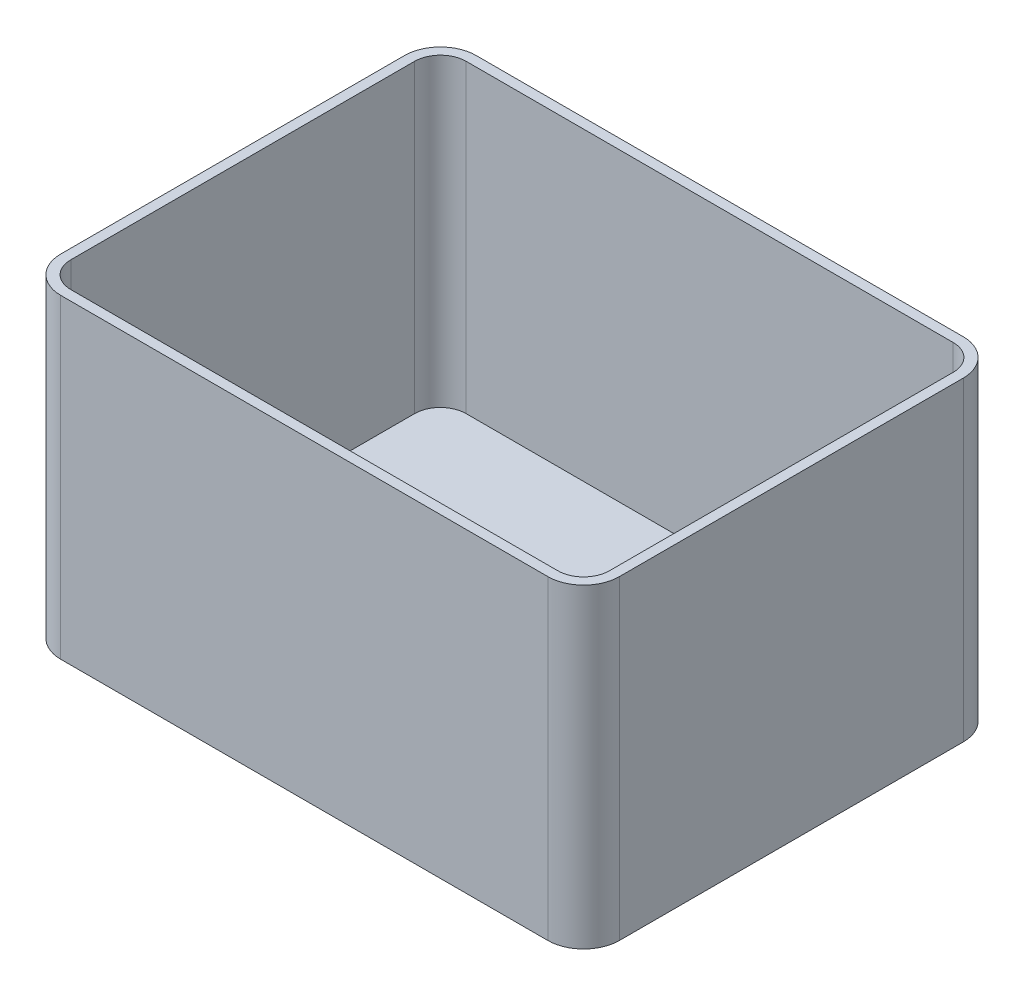
SolidWorks part; units mm, degrees
ref_plane "Front Plane" through (0, 0, 0) normal (0, 0, 1) x (1, 0, 0)
ref_plane "Top Plane" through (0, 0, 0) normal (0, 1, 0) x (1, 0, 0)
ref_plane "Right Plane" through (0, 0, 0) normal (1, 0, 0) x (0, 0, -1)
sketch "Sketch1" plane through (0, 0, 0) normal (0, 1, 0) x (1, 0, 0)
  line L1 (-170, -145) -> (170, -145)
  line L2 (-195, -120) -> (-195, 120)
  line L3 (-170, 145) -> (170, 145)
  line L4 (195, -120) -> (195, 120)
  line L5 (-195, -145) -> (195, 145) construction
  line L6 (-195, 145) -> (195, -145) construction
  arc A0 (170, 145) -> (195, 120) centre (170, 120) cw
  arc A1 (170, -145) -> (195, -120) centre (170, -120) ccw
  arc A2 (-170, -145) -> (-195, -120) centre (-170, -120) cw
  arc A3 (-195, 120) -> (-170, 145) centre (-170, 120) cw
  point P0 (0, 0)
  dimension "D3" = 25
  dimension "D1" = 390
  dimension "D2" = 290
extrude "Boss-Extrude1" add sketch "Sketch1" along normal blind 220
shell "Shell1" thickness 7
